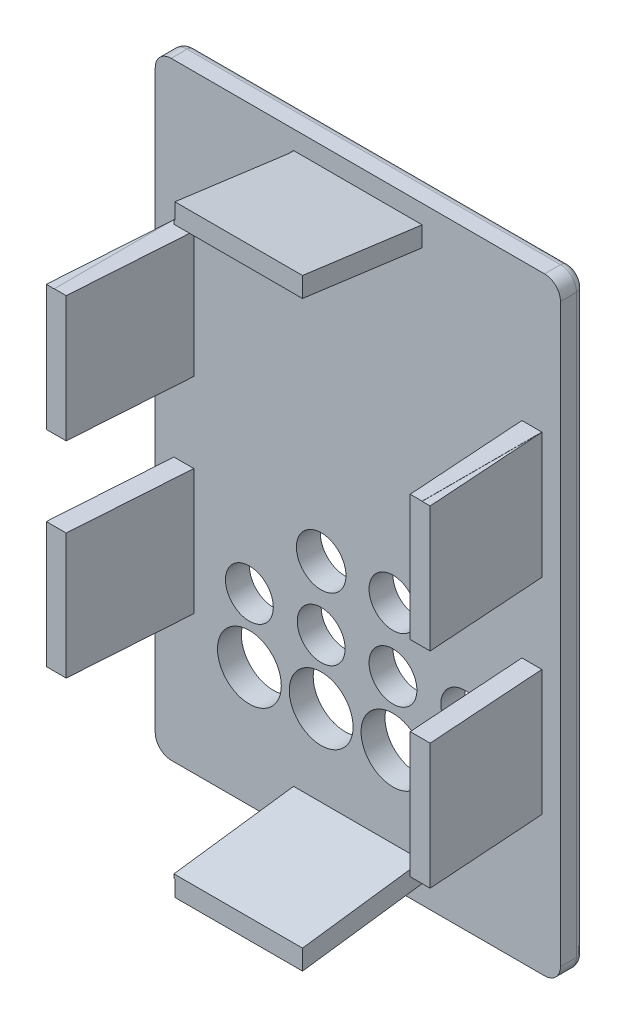
SolidWorks part; units mm, degrees
material "PLA"
ref_plane "Alzado" through (0, 0, 0) normal (0, 0, 1) x (1, 0, 0)
ref_plane "Planta" through (0, 0, 0) normal (0, 1, 0) x (1, 0, 0)
ref_plane "Vista lateral" through (0, 0, 0) normal (1, 0, 0) x (0, 0, -1)
sketch "Croquis1" plane through (0, 0, 0) normal (0, 0, 1) x (1, 0, 0)
  line L1 (25.4, 38.1) -> (-25.4, 38.1)
  line L2 (25.4, 38.1) -> (25.4, -38.1)
  line L3 (25.4, -38.1) -> (-25.4, -38.1)
  line L4 (-25.4, 38.1) -> (-25.4, -38.1)
  line L5 (25.4, 38.1) -> (-25.4, -38.1) construction
  line L6 (25.4, -38.1) -> (-25.4, 38.1) construction
  point P0 (0, 0)
  dimension "D1" = 76.2
  dimension "D2" = 50.8
extrude "Saliente-Extruir1" add sketch "Croquis1" along normal blind 18
sketch "Croquis2" plane through (0, 0, 18) normal (0, 0, 1) x (1, 0, 0)
  line L0 (25.4, 38.1) -> (-25.4, 38.1) construction
  line L1 (-23.06, 35.76) -> (23.06, 35.76)
  line L2 (-23.06, 35.76) -> (-23.06, -35.76)
  line L3 (-23.06, -35.76) -> (23.06, -35.76)
  line L4 (23.06, 35.76) -> (23.06, -35.76)
  line L5 (-25.4, -38.1) -> (25.4, -38.1) construction
  line L6 (-25.4, 38.1) -> (-25.4, -38.1) construction
  line L7 (25.4, -38.1) -> (25.4, 38.1) construction
  line L9 (-25.4, 38.1) -> (25.4, 38.1)
  line L10 (-25.4, 38.1) -> (-25.4, -38.1)
  line L11 (-25.4, -38.1) -> (25.4, -38.1)
  line L12 (25.4, 38.1) -> (25.4, -38.1)
  line L13 (-19.4, 32.1) -> (19.4, 32.1)
  line L14 (-19.4, 32.1) -> (-19.4, -32.1)
  line L15 (-19.4, -32.1) -> (19.4, -32.1)
  line L16 (19.4, 32.1) -> (19.4, -32.1)
  line M9 (-25.4, 38.1) -> (-25.4, -38.1)
  line M10 (-25.4, -38.1) -> (25.4, -38.1)
  line M11 (25.4, -38.1) -> (25.4, 38.1)
  line M12 (25.4, 38.1) -> (-25.4, 38.1)
  dimension "D1" = 2.34
  dimension "D2" = 2.34
  dimension "D3" = 2.34
  dimension "D4" = 2.34
  dimension "D5" = 6
  dimension "D6" = 6
  dimension "D7" = 6
  dimension "D8" = 6
extrude "Cortar-Extruir1" cut sketch "Croquis2" against normal blind 15 contours L1 L4 L3 L2 M12 M9 M10 M11 | L16 L13 L14 L15
sketch "Croquis3" plane through (0, 0, 18) normal (0, 0, 1) x (1, 0, 0)
  line L0 (-23.06, 35.76) -> (-23.06, -35.76) construction
  line L1 (-23.06, 22.1) -> (-19.4, 22.1)
  line L2 (-23.06, 22.1) -> (-23.06, -22.1)
  line L3 (-23.06, -22.1) -> (-19.4, -22.1)
  line L4 (-19.4, 22.1) -> (-19.4, -22.1)
  line L5 (-19.4, 32.1) -> (-19.4, -32.1) construction
  line L6 (-19.4, -32.1) -> (19.4, -32.1) construction
  line L7 (-9.4, -32.1) -> (9.3837, -32.1)
  line L8 (-9.4, -32.1) -> (-9.4, -35.76)
  line L9 (-9.4, -35.76) -> (9.3837, -35.76)
  line L10 (9.3837, -32.1) -> (9.3837, -35.76)
  line L11 (-23.06, -35.76) -> (23.06, -35.76) construction
  line L12 (19.4, 32.1) -> (19.4, -32.1) construction
  line L13 (19.4, -22.1) -> (23.06, -22.1)
  line L14 (19.4, -22.1) -> (19.4, 22.1)
  line L15 (19.4, 22.1) -> (23.06, 22.1)
  line L16 (23.06, -22.1) -> (23.06, 22.1)
  line L17 (23.06, 35.76) -> (23.06, -35.76) construction
  line L18 (-23.06, 35.76) -> (23.06, 35.76) construction
  line L19 (-9.4, 35.76) -> (9.4, 35.76)
  line L20 (-9.4, 35.76) -> (-9.4, 32.1)
  line L21 (-9.4, 32.1) -> (9.4, 32.1)
  line L22 (9.4, 35.76) -> (9.4, 32.1)
  line L23 (-19.4, 32.1) -> (19.4, 32.1) construction
  line L24 (-19.4, 32.1) -> (-19.4, -32.1) construction
  line L25 (19.4, 32.1) -> (19.4, -32.1) construction
  dimension "D1" = 10
  dimension "D2" = 10
  dimension "D3" = 10
  dimension "D4" = 10
  dimension "D5" = 10
  dimension "D6" = 10
  dimension "D7" = 10
extrude "Cortar-Extruir2" [suppressed] cut sketch "Croquis3" against normal blind 7
fillet "Redondeo1" [suppressed] radius 2
fillet "Redondeo2" [suppressed] radius 1
sketch "Croquis5" [suppressed] plane through (0, -38.1, 0) normal (0, -1, 0) x (1, 0, 0)
  line L0 (-23.4, 3) -> (23.4, 3) construction
  line L1 (-3, 3) -> (3, 3)
  line L2 (-3, 3) -> (-3, 1.5)
  line L3 (-3, 1.5) -> (3, 1.5)
  line L4 (3, 3) -> (3, 1.5)
  line L5 (0, 1) -> (0, 3) construction
  line L6 (-23.4, 1) -> (23.4, 1) construction
  dimension "D1" = 3
  dimension "D2" = 3
  dimension "D3" = 1.5
extrude "Cortar-Extruir4" [suppressed] cut sketch "Croquis5" against normal blind 6
sketch "Croquis6" plane through (0, 0, 18) normal (0, 0, 1) x (1, 0, 0)
  line L0 (-23.06, 35.76) -> (-8.06, 35.76)
  line L1 (-23.06, 35.76) -> (23.06, 35.76) construction
  line L2 (-8.06, 35.76) -> (-8.06, 32.1)
  line L3 (-19.4, 32.1) -> (19.4, 32.1) construction
  line L4 (-8.06, 32.1) -> (-19.4, 32.1)
  line L5 (-19.4, 32.1) -> (-19.4, 20.76)
  line L6 (-19.4, 32.1) -> (-19.4, -32.1) construction
  line L7 (-19.4, 20.76) -> (-23.06, 20.76)
  line L8 (-23.06, 35.76) -> (-23.06, -35.76) construction
  line L9 (-23.06, 20.76) -> (-23.06, 35.76)
  line L10 (23.06, 35.76) -> (8.06, 35.76)
  line L11 (-23.06, 35.76) -> (23.06, 35.76) construction
  line L12 (8.06, 35.76) -> (8.06, 32.1)
  line L13 (8.06, 32.1) -> (19.4, 32.1)
  line L14 (19.4, 32.1) -> (19.4, -32.1) construction
  line L15 (19.4, 32.1) -> (19.4, -32.1) construction
  line L16 (19.4, 32.1) -> (19.4, 20.76)
  line L17 (19.4, 20.76) -> (23.06, 20.76)
  line L18 (23.06, 35.76) -> (23.06, -35.76) construction
  line L19 (23.06, 20.76) -> (23.06, 35.76)
  line L20 (-23.06, -35.76) -> (-23.06, -20.76)
  line L21 (-23.06, 35.76) -> (-23.06, -35.76) construction
  line L22 (-23.06, -20.76) -> (-19.4, -20.76)
  line L23 (-19.4, 32.1) -> (-19.4, -32.1) construction
  line L24 (-19.4, -20.76) -> (-19.4, -32.1)
  line L25 (-19.4, -32.1) -> (-8.06, -32.1)
  line L26 (-19.4, -32.1) -> (19.4, -32.1) construction
  line L27 (-8.06, -32.1) -> (-8.06, -35.76)
  line L28 (-23.06, -35.76) -> (23.06, -35.76) construction
  line L29 (-8.06, -35.76) -> (-23.06, -35.76)
  line L30 (23.06, -35.76) -> (8.06, -35.76)
  line L31 (-23.06, -35.76) -> (23.06, -35.76) construction
  line L32 (8.06, -35.76) -> (8.06, -32.1)
  line L33 (-19.4, -32.1) -> (19.4, -32.1) construction
  line L34 (8.06, -32.1) -> (19.4, -32.1)
  line L35 (19.4, -32.1) -> (19.4, -20.76)
  line L36 (19.4, -20.76) -> (23.06, -20.76)
  line L37 (23.06, 35.76) -> (23.06, -35.76) construction
  line L38 (23.06, -20.76) -> (23.06, -35.76)
  dimension "D1" = 15
  dimension "D2" = 15
  dimension "D3" = 15
  dimension "D4" = 15
  dimension "D5" = 15
  dimension "D6" = 15
  dimension "D7" = 15
  dimension "D8" = 15
extrude "Cortar-Extruir8" cut sketch "Croquis6" against normal blind 15
sketch "Croquis10" plane through (0, -20.76, 0) normal (0, -1, 0) x (-1, 0, 0)
  line L0 (23.06, -18) -> (24.06, -18)
  line L1 (24.06, -18) -> (23.06, -3)
  line L2 (23.06, -3) -> (23.06, -18)
  line L3 (-23.06, -18) -> (-24.06, -18)
  line L4 (-24.06, -18) -> (-23.06, -3)
  line L5 (-23.06, -3) -> (-23.06, -18)
  dimension "D1" = 1
  dimension "D2" = 1
extrude "Saliente-Extruir3" add sketch "Croquis10" against normal blind 41.5
sketch "Croquis11" plane through (0, -20.76, 0) normal (0, -1, 0) x (1, 0, 0)
  line L0 (-19.4, 18) -> (-21.56, 18)
  line L1 (-19.4, 18) -> (-24.06, 18) construction
  line L2 (-21.56, 18) -> (-20.56, 3)
  line L3 (-19.4, 3) -> (-23.06, 3) construction
  line L4 (-20.56, 3) -> (-19.4, 3)
  line L5 (-19.4, 18) -> (-19.4, 3)
  dimension "D1" = 2.5
  dimension "D2" = 1.16
extrude "Cortar-Extruir9" cut sketch "Croquis11" against normal blind 51.5
sketch "Croquis12" plane through (0, -20.76, 0) normal (0, -1, 0) x (1, 0, 0)
  line L0 (19.4, 18) -> (19.4, 3)
  line L1 (19.4, 3) -> (20.56, 3)
  line L2 (23.06, 3) -> (19.4, 3) construction
  line L3 (20.56, 3) -> (21.56, 18)
  line L4 (24.06, 18) -> (19.4, 18) construction
  line L5 (21.56, 18) -> (19.4, 18)
  dimension "D1" = 2.5
  dimension "D2" = 1.16
extrude "Cortar-Extruir10" cut sketch "Croquis12" against normal blind 51.5
sketch "Croquis13" plane through (8.06, 0, 0) normal (1, 0, 0) x (0, 0, -1)
  line L0 (-18, -35.76) -> (-18, -37.76)
  line L1 (-18, -37.76) -> (-3, -35.76)
  line L2 (-3, -35.76) -> (-18, -35.76)
  line L3 (-18, 35.76) -> (-18, 37.76)
  line L4 (-18, 37.76) -> (-3, 35.76)
  line L5 (-3, 35.76) -> (-18, 35.76)
  dimension "D1" = 2
  dimension "D2" = 2
extrude "Saliente-Extruir4" add sketch "Croquis13" against normal blind 16
sketch "Croquis14" plane through (8.06, 0, 0) normal (1, 0, 0) x (0, 0, -1)
  line L0 (-3, -32.1) -> (-18, -32.1)
  line L1 (-18, -32.1) -> (-18, -35.26)
  line L2 (-18, -32.1) -> (-18, -37.76) construction
  line L3 (-18, -35.26) -> (-3, -33.26)
  line L4 (-3, -32.1) -> (-3, -35.76) construction
  line L5 (-3, -33.26) -> (-3, -32.1)
  line L6 (-18, 32.1) -> (-18, 35.26)
  line L7 (-18, 37.76) -> (-18, 32.1) construction
  line L8 (-18, 35.26) -> (-3, 33.26)
  line L9 (-3, 35.76) -> (-3, 32.1) construction
  line L10 (-3, 33.26) -> (-3, 32.1)
  line L11 (-3, 32.1) -> (-18, 32.1)
  dimension "D1" = 2.5
  dimension "D2" = 1.16
  dimension "D3" = 2.5
  dimension "D4" = 1.16
extrude "Cortar-Extruir11" cut sketch "Croquis14" against normal blind 16.5
fillet "Redondeo3" radius 2 4 edges at (25.4, 38.1, 1.5) (-25.4, 38.1, 1.5) (-25.4, -38.1, 1.5) (25.4, -38.1, 1.5)
fillet "Redondeo4" radius 1 8 edges at (-24.8142, 37.5142, 0) (-25.4, 0, 0) (-24.8142, -37.5142, 0) (0, -38.1, 0) (24.8142, -37.5142, 0) (25.4, 0, 0) (24.8142, 37.5142, 0) (0, 38.1, 0)
sketch "Croquis15" plane through (0, 0, 18) normal (0, 0, 1) x (1, 0, 0)
  line L0 (-24.06, -0.01) -> (24.06, -0.01) construction
  line L1 (-24.06, 20.74) -> (-24.06, -20.76) construction
  line L2 (24.06, 20.74) -> (24.06, -20.76) construction
  line L4 (-24.06, 4.99) -> (24.06, 4.99)
  line L5 (-24.06, 4.99) -> (-24.06, -5.01)
  line L6 (-24.06, -5.01) -> (24.06, -5.01)
  line L7 (24.06, 4.99) -> (24.06, -5.01)
  dimension "D1" = 5
  dimension "D2" = 5
extrude "Cortar-Extruir12" cut sketch "Croquis15" against normal blind 15
sketch "Croquis16" plane through (0, -38.1, 0) normal (0, -1, 0) x (1, 0, 0)
  line L0 (-23.4, 3) -> (23.4, 3) construction
  line L1 (-4, 3) -> (4, 3)
  line L2 (-4, 3) -> (-4, 1.5)
  line L3 (-4, 1.5) -> (4, 1.5)
  line L4 (4, 3) -> (4, 1.5)
  dimension "D1" = 1.5
  dimension "D2" = 8
  dimension "D3" = 4
extrude "Cortar-Extruir13" cut sketch "Croquis16" against normal blind 2
sketch "Croquis17" plane through (0, 0, 3) normal (0, 0, 1) x (1, 0, 0)
  line L0 (-4, -38.1) -> (4, -38.1) construction
  line L1 (-23.4, -38.1) -> (-4, -38.1) construction
  line L2 (25.4, -36.1) -> (25.4, 36.1) construction
  line L3 (4, -38.1) -> (23.4, -38.1) construction
  circle A0 centre (13.4, -23.1) radius 4
  circle A1 centre (13.4, -15.1) radius 3
  circle A2 centre (4.4, -23.1) radius 4
  circle A3 centre (-4.6, -23.1) radius 4
  circle A4 centre (-13.6, -23.1) radius 4
  circle A5 centre (4.4, -15.1) radius 3
  circle A6 centre (-4.6, -15.1) radius 3
  circle A7 centre (-13.6, -15.1) radius 3
  circle A8 centre (-4.6, -7.1) radius 3.1051
  circle A9 centre (4.4, -7.1) radius 3.0016
  dimension "D3" = 8
  dimension "D4" = 6
  dimension "D5" = 8
  dimension "D10" = 8
  dimension "D11" = 8
  dimension "D14" = 15
  dimension "D22" = 6
  dimension "D23" = 6
  dimension "D24" = 6
  dimension "D27" = 6.0033
  dimension "D28" = 6.2103
  dimension "D1" = 12
  dimension "D2" = 15
  dimension "D6" = 9
  dimension "D7" = 8
  dimension "D8" = 12
  dimension "D9" = 15
  dimension "D12" = 9
  dimension "D13" = 9
  dimension "D15" = 15
  dimension "D16" = 8
  dimension "D17" = 8
  dimension "D18" = 8
  dimension "D19" = 9
  dimension "D20" = 9
  dimension "D21" = 9
  dimension "D25" = 8
  dimension "D26" = 8
  dimension "D29" = 9
  dimension "D30" = 9
extrude "Cortar-Extruir14" cut sketch "Croquis17" against normal blind 10
